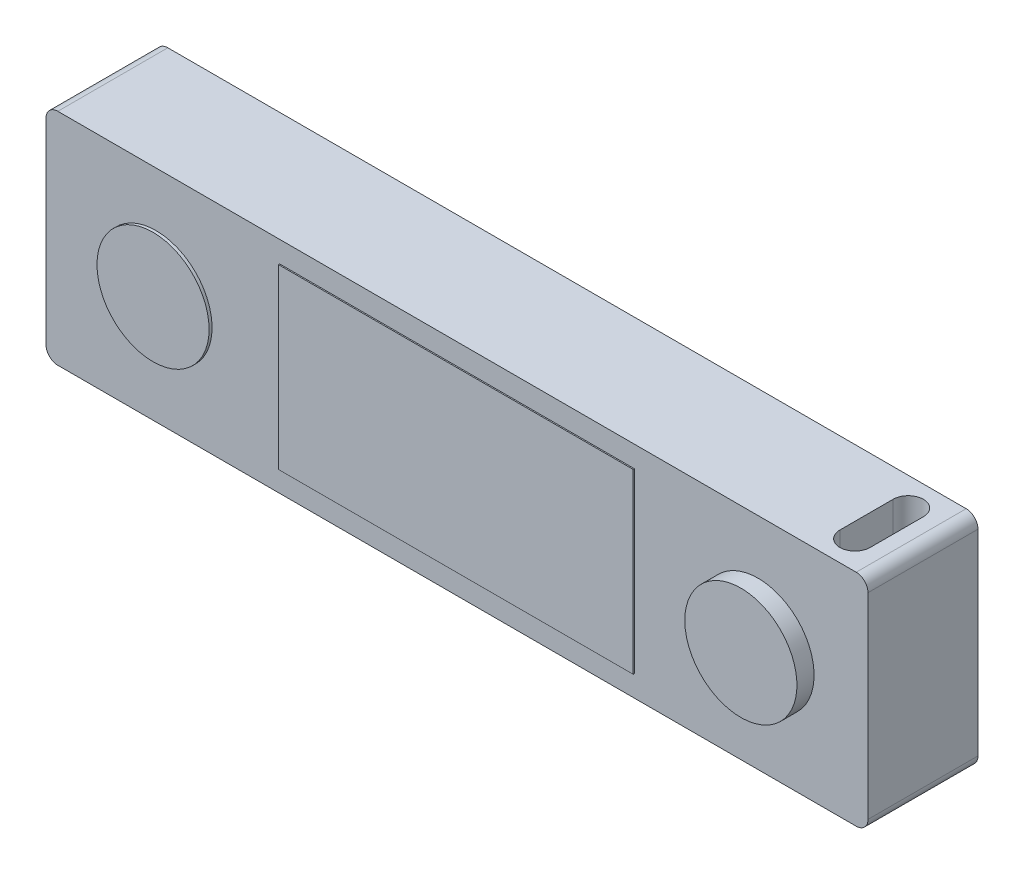
SolidWorks part; units mm, degrees
material "Plastique personnalisé"
ref_plane "Plan de face" through (0, 0, 0) normal (0, 0, 1) x (1, 0, 0)
ref_plane "Plan de dessus" through (0, 0, 0) normal (0, 1, 0) x (1, 0, 0)
ref_plane "Plan de droite" through (0, 0, 0) normal (1, 0, 0) x (0, 0, -1)
sketch "Esquisse1" plane through (0, 0, 0) normal (0, 0, 1) x (1, 0, 0)
  line L1 (-34.75, -9.3) -> (34.75, -9.3)
  line L2 (-34.75, -9.3) -> (-34.75, 9.3)
  line L3 (-34.75, 9.3) -> (34.75, 9.3)
  line L4 (34.75, -9.3) -> (34.75, 9.3)
  line L5 (-34.75, -9.3) -> (34.75, 9.3) construction
  line L6 (-34.75, 9.3) -> (34.75, -9.3) construction
  point P0 (0, 0)
  dimension "D1" = 69.5
  dimension "D2" = 18.6
extrude "Boss.-Extru.1" add sketch "Esquisse1" along normal blind 9.3
sketch "Esquisse2" plane through (0, 9.3, 0) normal (0, 1, 0) x (1, 0, 0)
  line L0 (34.75, -4.65) -> (31.2507, -4.65) construction
  line L1 (34.75, -9.3) -> (34.75, 0) construction
  line L2 (31.2507, -6.9006) -> (31.2507, -2.3994) construction
  line L3 (29.9712, -6.9006) -> (29.9712, -2.3994)
  line L4 (32.5302, -6.9006) -> (32.5302, -2.3994)
  arc A0 (29.9712, -6.9006) -> (32.5302, -6.9006) centre (31.2507, -6.9006) ccw
  arc A1 (32.5302, -2.3994) -> (29.9712, -2.3994) centre (31.2507, -2.3994) ccw
  point P6 (31.2507, -4.65)
extrude "Enlèv. mat.-Extru.1" cut sketch "Esquisse2" against normal through all both and the other way through all
fillet "Congé1" radius 1 4 edges at (-34.75, -9.3, 4.65) (-34.75, 9.3, 4.65) (34.75, -9.3, 4.65) (34.75, 9.3, 4.65)
ref_plane "Plan1" through (0, 0, 4.65) normal (0, 0, 1) x (1, 0, 0)
sketch "Esquisse3" plane through (0, 0, 9.3) normal (0, 0, 1) x (1, 0, 0)
  circle A0 centre (25.45, -0.024) radius 4.74
extrude "Boss.-Extru.2" add sketch "Esquisse3" along normal up to surface (1.45 mm away)
sketch "Esquisse4" plane through (0, 0, 9.3) normal (0, 0, 1) x (1, 0, 0)
  line L0 (0, 9.3) -> (0, -9.3) construction
  line L1 (33.75, 9.3) -> (-33.75, 9.3) construction
  line L2 (-33.75, -9.3) -> (33.75, -9.3) construction
  line L3 (25.45, -0.024) -> (0, 0) construction
  line L4 (-25.45, -0.024) -> (0, 0) construction
  circle A0 centre (-25.45, -0.024) radius 4.74
extrude "Boss.-Extru.3" add sketch "Esquisse4" along normal blind 0.25
sketch "Esquisse5" plane through (0, 0, 9.3) normal (0, 0, 1) x (1, 0, 0)
  line L0 (25.45, -0.024) -> (-25.45, -0.024) construction
  line L2 (-15, -7.5) -> (15, -7.5)
  line L3 (-15, -7.5) -> (-15, 7.5)
  line L4 (-15, 7.5) -> (15, 7.5)
  line L5 (15, -7.5) -> (15, 7.5)
  line L6 (-15, -7.5) -> (15, 7.5) construction
  line L7 (-15, 7.5) -> (15, -7.5) construction
  point P4 (0, 0)
  dimension "D1" = 30
  dimension "D2" = 15
extrude "Boss.-Extru.4" add sketch "Esquisse5" along normal blind 0.1
